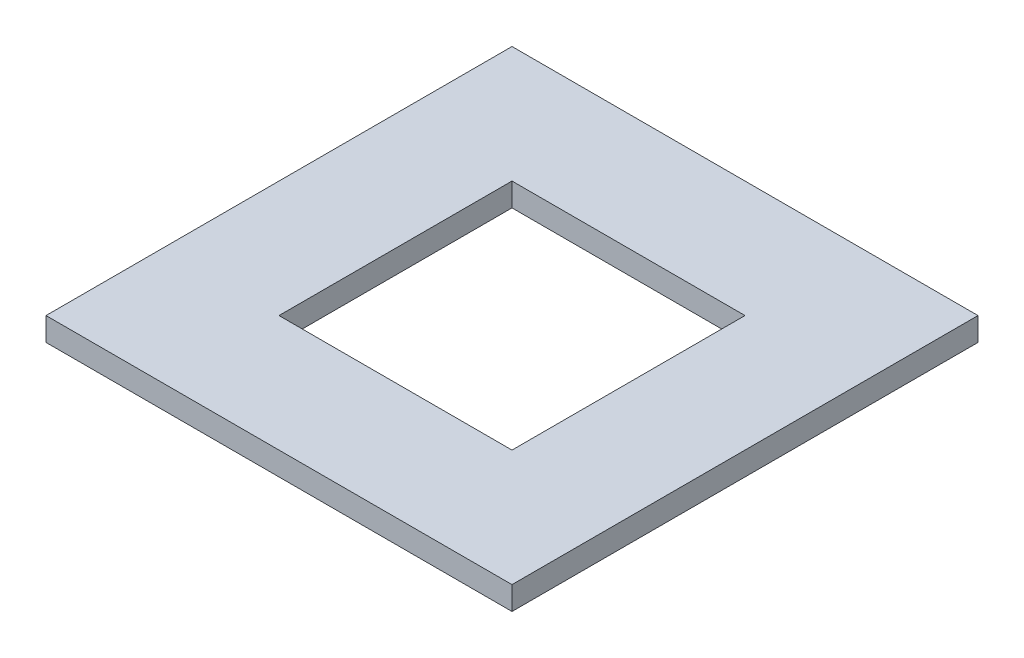
SolidWorks part; units mm, degrees
ref_plane "Front Plane" through (0, 0, 0) normal (0, 0, 1) x (1, 0, 0)
ref_plane "Top Plane" through (0, 0, 0) normal (0, 1, 0) x (1, 0, 0)
ref_plane "Right Plane" through (0, 0, 0) normal (1, 0, 0) x (0, 0, -1)
sketch "Sketch1" plane through (0, 0, 0) normal (0, 1, 0) x (1, 0, 0)
  line L0 (-100, 100) -> (-100, -100)
  line L1 (-50, 50) -> (50, 50)
  line L2 (-50, 50) -> (-50, -50)
  line L3 (-50, -50) -> (50, -50)
  line L4 (50, 50) -> (50, -50)
  line L5 (-50, 50) -> (50, -50) construction
  line L6 (-50, -50) -> (50, 50) construction
  line L7 (-100, -100) -> (100, -100)
  line L8 (100, 100) -> (100, -100)
  line L9 (-100, 100) -> (100, 100)
  point P0 (0, 0)
  dimension "D1" = 100
  dimension "D2" = 100
  dimension "D3" = 50
extrude "Boss-Extrude1" add sketch "Sketch1" along normal blind 10
